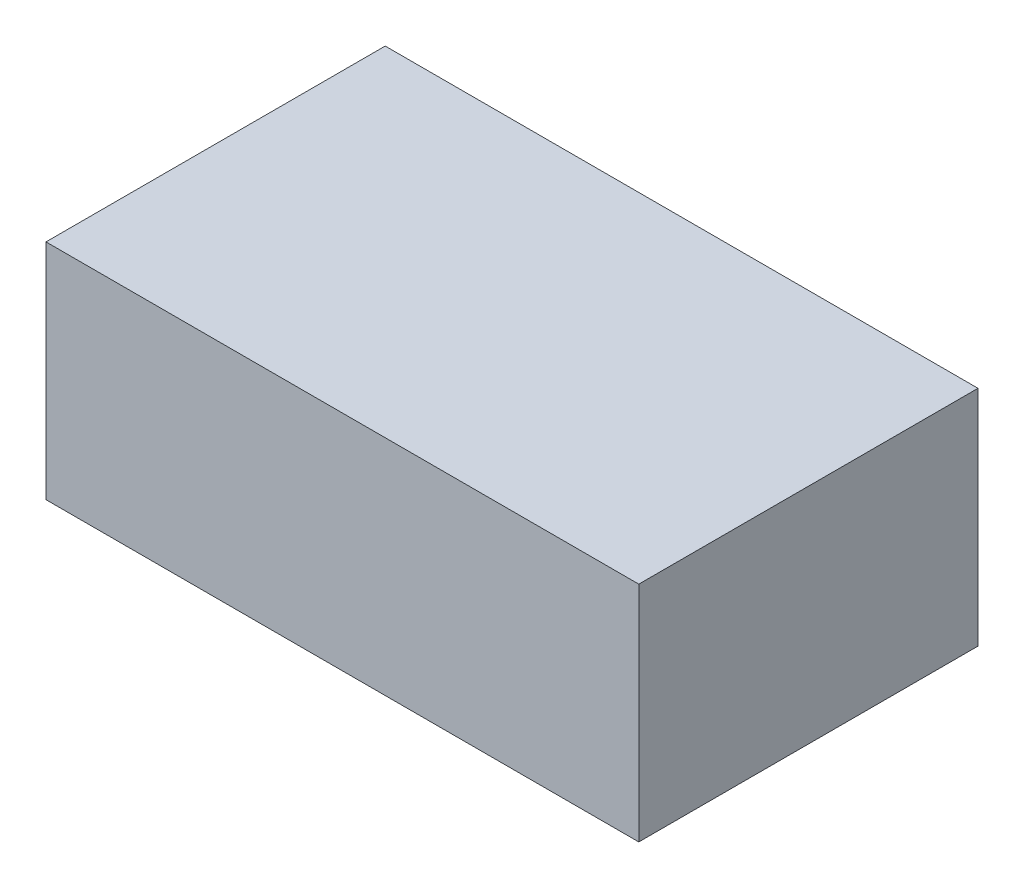
SolidWorks part; units mm, degrees
ref_plane "Front Plane" through (0, 0, 0) normal (0, 0, 1) x (1, 0, 0)
ref_plane "Top Plane" through (0, 0, 0) normal (0, 1, 0) x (1, 0, 0)
ref_plane "Right Plane" through (0, 0, 0) normal (1, 0, 0) x (0, 0, -1)
sketch "Sketch1" plane through (0, 0, 0) normal (0, 1, 0) x (1, 0, 0)
  line L1 (0, 0) -> (45.72, 0)
  line L2 (0, 0) -> (0, -26.162)
  line L3 (0, -26.162) -> (45.72, -26.162)
  line L4 (45.72, 0) -> (45.72, -26.162)
  dimension "D1" = 26.162
  dimension "D2" = 45.72
extrude "Boss-Extrude1" add sketch "Sketch1" along normal blind 17.2212
